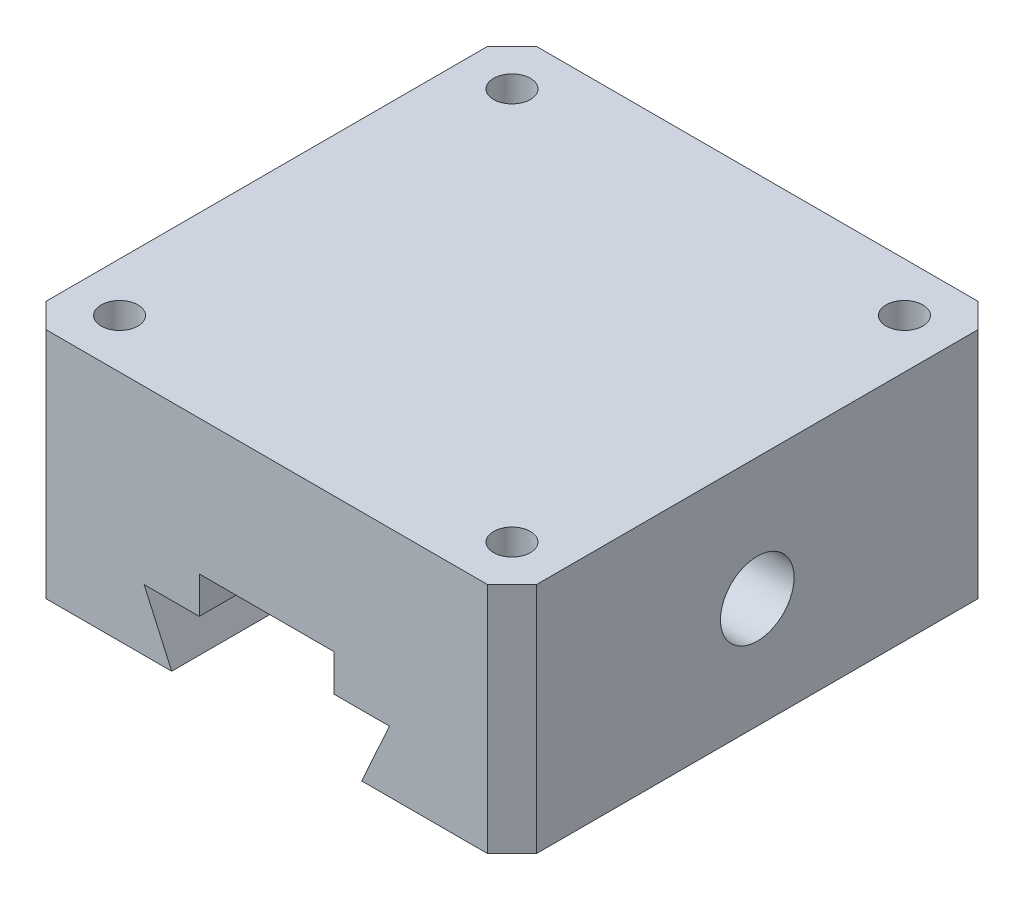
SolidWorks part; units mm, degrees
material "6061"
ref_plane "前视基准面" through (0, 0, 0) normal (0, 0, 1) x (1, 0, 0)
ref_plane "上视基准面" through (0, 0, 0) normal (0, 1, 0) x (1, 0, 0)
ref_plane "右视基准面" through (0, 0, 0) normal (1, 0, 0) x (0, 0, -1)
sketch "草图1" plane through (0, 0, 0) normal (0, 0, 1) x (1, 0, 0)
  line L0 (-10, 5) -> (10, 5)
  line L1 (0, 0) -> (0, 5) construction
  line L2 (-10, 5) -> (-7.75, 0)
  line L3 (-7.75, 0) -> (-20, 0)
  line L4 (-20, 0) -> (-20, 19)
  line L5 (-20, 19) -> (20, 19)
  line L6 (20, 0) -> (20, 19)
  line L7 (7.75, 0) -> (20, 0)
  line L8 (10, 5) -> (7.75, 0)
  point P9 (0, 19)
  dimension "D1" = 20
  dimension "D2" = 5
  dimension "D3" = 15.5
  dimension "D4" = 19
  dimension "D5" = 40
extrude "凸台-拉伸1" add sketch "草图1" along normal mid plane 40
sketch "草图4" plane through (0, 19, 0) normal (0, 1, 0) x (1, 0, 0)
  line L1 (25, -25) -> (-25, -25) construction
  line L2 (25, -25) -> (25, 25) construction
  line L3 (25, 25) -> (-25, 25) construction
  line L4 (-25, -25) -> (-25, 25) construction
  line L5 (25, -25) -> (-25, 25) construction
  line L6 (25, 25) -> (-25, -25) construction
  point P0 (0, 0)
  dimension "D1" = 50
  dimension "D2" = 50
sketch "草图8" plane through (0, 0, -20) normal (0, 0, -1) x (-1, 0, 0)
  line L0 (0, 0) -> (0, 20.119) construction
  line L1 (10, 5) -> (-10, 5) construction
  line L2 (5.5, 2) -> (-5.5, 2)
  line L3 (5.5, 2) -> (5.5, 8)
  line L4 (5.5, 8) -> (-5.5, 8)
  line L5 (-5.5, 2) -> (-5.5, 8)
  line L6 (5.5, 2) -> (-5.5, 8) construction
  line L7 (5.5, 8) -> (-5.5, 2) construction
  point P3 (0, 5)
  dimension "D1" = 11
  dimension "D2" = 3
extrude "切除-拉伸1" cut sketch "草图8" against normal up to next
sketch "草图10" plane through (-20, 0, 0) normal (-1, 0, 0) x (0, 0, 1)
  circle A0 centre (0, 6) radius 1.6062 construction
  dimension "D1" = 6
hole_wizard "M6 螺纹孔3" positions "草图12" profile "草图11" tap size "M6" standard "GB"
sketch "草图12" plane through (-20, 0, 0) normal (-1, 0, 0) x (0, 0, 1)
  point P0 (0, 6)
sketch "草图11" plane through (-20, 6, 0) normal (0, 1, 0) x (0, 0, 1)
  line L0 (0, 0) -> (0, 36.5022)
  line L1 (0, 36.5022) -> (2.5, 35)
  line L2 (2.5, 35) -> (2.5, 0.525)
  line L3 (2.5, 0.525) -> (3.025, 0)
  line L5 (3.025, 0) -> (0, 0)
  line L6 (-2.5, 0.525) -> (-3.025, 0) construction
  line L10 (0, 36.5022) -> (-2.5, 35) construction
  line L11 (0, -6.35) -> (0, 107.95) construction
  dimension "螺纹孔钻头直径" = 5
  dimension "螺纹孔钻头深度" = 35
  dimension "近端锥形沉头孔直径" = 6.05
  dimension "近端锥形沉头孔角度" = 90
  dimension "导头角度" = 118
sketch "草图13" plane through (20, 0, 0) normal (1, 0, 0) x (0, 0, -1)
  line L0 (-20, 19) -> (20, 19) construction
  circle A0 centre (0, 9) radius 3
  dimension "D2" = 6
  dimension "D1" = 10
extrude "切除-拉伸2" cut sketch "草图13" against normal blind 45
sketch "草图14" plane through (0, 8, 0) normal (0, -1, 0) x (1, 0, 0)
  line L0 (0, 5.5) -> (0, -5.5) construction
  line L1 (5.5, 5.5) -> (5.5, -5.5)
  line L2 (-5.5, 5.5) -> (-5.5, -5.5)
  line L3 (-5.5, -2.8284) -> (-5.5, -20) construction
  arc A0 (5.5, 5.5) -> (-5.5, 5.5) centre (0, 5.5) ccw
  arc A1 (-5.5, -5.5) -> (5.5, -5.5) centre (0, -5.5) ccw
  point P2 (0, 0)
  dimension "D1" = 22
extrude "切除-拉伸3" cut sketch "草图14" against normal blind 7
chamfer "倒角1" distance 2 angle 45 4 edges at (-20, 9.5, -20) (20, 9.5, -20) (20, 9.5, 20) (-20, 9.5, 20)
sketch "草图15" plane through (0, 19, 0) normal (0, 1, 0) x (1, 0, 0)
  line L1 (-16, 16) -> (16, 16) construction
  line L2 (-16, 16) -> (-16, -16) construction
  line L3 (-16, -16) -> (16, -16) construction
  line L4 (16, 16) -> (16, -16) construction
  line L5 (-16, 16) -> (16, -16) construction
  line L6 (-16, -16) -> (16, 16) construction
  circle A0 centre (-16, 16) radius 1.5
  circle A1 centre (16, 16) radius 1.5
  circle A2 centre (16, -16) radius 1.5
  circle A3 centre (-16, -16) radius 1.5
  point P0 (0, 0)
  dimension "D3" = 3
  dimension "D4" = 3
  dimension "D5" = 3
  dimension "D6" = 3
  dimension "D1" = 32
  dimension "D2" = 32
extrude "切除-拉伸4" cut sketch "草图15" against normal blind 10
